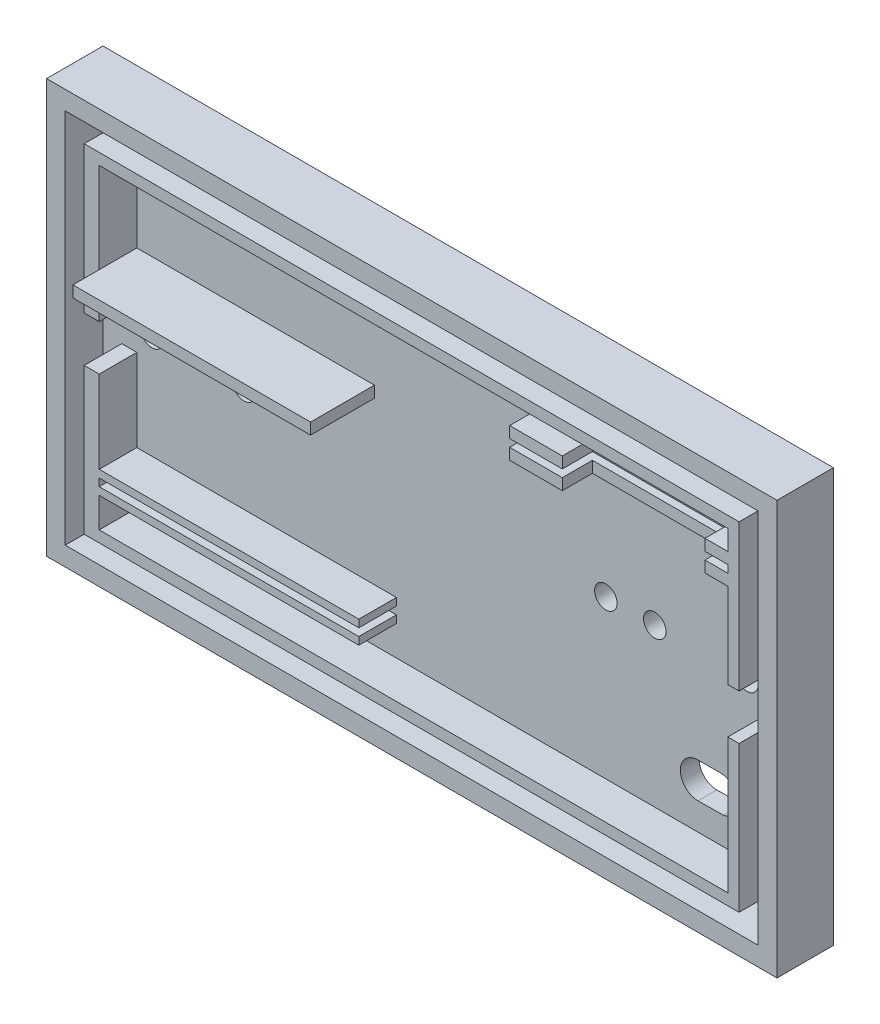
SolidWorks part; units mm, degrees
ref_plane "Plano frontal" through (0, 0, 0) normal (0, 0, 1) x (1, 0, 0)
ref_plane "Plano superior" through (0, 0, 0) normal (0, 1, 0) x (1, 0, 0)
ref_plane "Plano direito" through (0, 0, 0) normal (1, 0, 0) x (0, 0, -1)
sketch "Esboço1" plane through (0, 0, 0) normal (0, 0, 1) x (1, 0, 0)
  line L1 (-72.1599, 32.7405) -> (102.0401, 32.7405)
  line L2 (-72.1599, 32.7405) -> (-72.1599, -57.2595)
  line L3 (-72.1599, -57.2595) -> (102.0401, -57.2595)
  line L4 (102.0401, 32.7405) -> (102.0401, -57.2595)
  dimension "D1" = 174.2
  dimension "D2" = 90
extrude "Ressalto-extrusão1" add sketch "Esboço1" along normal blind 10
sketch "Esboço2" plane through (0, 0, 0) normal (0, 0, -1) x (-1, 0, 0)
  line L0 (-102.0401, 32.7405) -> (72.1599, 32.7405) construction
  line L1 (82.1599, 42.7405) -> (-112.0401, 42.7405)
  line L2 (82.1599, 42.7405) -> (82.1599, -67.2595)
  line L3 (82.1599, -67.2595) -> (-112.0401, -67.2595)
  line L4 (-112.0401, 42.7405) -> (-112.0401, -67.2595)
  line L5 (72.1599, 32.7405) -> (72.1599, -57.2595) construction
  line L6 (-102.0401, -57.2595) -> (-102.0401, 32.7405) construction
  line L7 (72.1599, -57.2595) -> (-102.0401, -57.2595) construction
  line L13 (77.1999, 37.7805) -> (-107.0001, 37.7805)
  line L14 (77.1999, 37.7805) -> (77.1999, -62.2195)
  line L15 (77.1999, -62.2195) -> (-107.0001, -62.2195)
  line L16 (-107.0001, 37.7805) -> (-107.0001, -62.2195)
  point P16 (72.1599, -12.2595)
  dimension "D1" = 10
  dimension "D2" = 10
  dimension "D3" = 10
  dimension "D4" = 10
  dimension "D5" = 5.04
  dimension "D6" = 5.04
  dimension "D7" = 5.04
  dimension "D8" = 5.04
extrude "Ressalto-extrusão2" add sketch "Esboço2" against normal blind 20 separate body
sketch "Esboço3" plane through (0, 0, 0) normal (0, 0, -1) x (-1, 0, 0)
  line L1 (82.1599, 42.7405) -> (-112.0401, 42.7405)
  line L2 (82.1599, 42.7405) -> (82.1599, -67.2595)
  line L3 (82.1599, -67.2595) -> (-112.0401, -67.2595)
  line L4 (-112.0401, 42.7405) -> (-112.0401, -67.2595)
extrude "Ressalto-extrusão3" add sketch "Esboço3" along normal blind 5
sketch "Esboço5" plane through (0, 0, 10) normal (0, 0, 1) x (1, 0, 0)
  line L0 (-72.1599, 32.7405) -> (-72.1599, -57.2595) construction
  line L1 (102.0401, -57.2595) -> (102.0401, 32.7405) construction
  line L2 (-102.7254, -12.2595) -> (207.6233, -12.2595) construction
  line L3 (-72.1599, -57.2595) -> (102.0401, -57.2595) construction
  line L4 (-72.1599, 32.7405) -> (-72.1599, -57.2595) construction
  line L6 (102.0401, 32.7405) -> (-72.1599, 32.7405) construction
  line L10 (102.0401, -57.2595) -> (102.0401, 32.7405) construction
  circle A0 centre (-64.1599, -12.2595) radius 3
  circle A1 centre (94.0401, -12.2595) radius 3
  circle A2 centre (-39.6599, -12.2595) radius 3
  circle A3 centre (69.5401, -12.2595) radius 3
  circle A4 centre (56.5401, -12.2595) radius 3
  dimension "D1" = 8
  dimension "D5" = 32.5
  dimension "D8" = 6
  dimension "D9" = 6
  dimension "D12" = 6
  dimension "D11" = 6
  dimension "D14" = 6
  dimension "D2" = 8
  dimension "D3" = 45
  dimension "D4" = 45
  dimension "D6" = 32.5
  dimension "D10" = 45
  dimension "D13" = 13
  dimension "D15" = 45
extrude "Corte-extrusão1" cut sketch "Esboço5" against normal blind 20
sketch3d "3DSketch1"
  point P0 (-63.0804, 12.5723, 10)
ref_plane "Plano1" through (0, 0, 10) normal (0, 0, 1) x (1, 0, 0)
sketch "Esboço6" plane through (0, 0, 10) normal (0, 0, 1) x (1, 0, 0)
  line L1 (-68.1599, 5.7405) -> (-4.9785, 5.7405)
  line L2 (-68.1599, 5.7405) -> (-68.1599, 2.7405)
  line L3 (-68.1599, 2.7405) -> (-4.9785, 2.7405)
  line L4 (-4.9785, 5.7405) -> (-4.9785, 2.7405)
  line L5 (102.0401, 32.7405) -> (-72.1599, 32.7405) construction
  line L6 (-72.1599, 32.7405) -> (-72.1599, -57.2595) construction
  dimension "D1" = 27
  dimension "3" = 3
  dimension "D2" = 4
extrude "Ressalto-extrusão4" add sketch "Esboço6" along normal blind 17
sketch "Esboço7" plane through (0, 0, 10) normal (0, 0, 1) x (1, 0, 0)
  line L1 (-69.1499, -42.2298) -> (0.8501, -42.2298)
  line L2 (-69.1499, -42.2298) -> (-69.1499, -40.2298)
  line L3 (-69.1499, -40.2298) -> (0.8501, -40.2298)
  line L4 (0.8501, -42.2298) -> (0.8501, -40.2298)
  line L6 (-69.1499, -46.2298) -> (0.8501, -46.2298)
  line L7 (-69.1499, -46.2298) -> (-69.1499, -44.2298)
  line L8 (-69.1499, -44.2298) -> (0.8501, -44.2298)
  line L9 (0.8501, -46.2298) -> (0.8501, -44.2298)
  line L10 (98.9601, 16.4084) -> (40.9601, 16.4084)
  line L11 (98.9601, 16.4084) -> (98.9601, 19.4084)
  line L12 (98.9601, 19.4084) -> (40.9601, 19.4084)
  line L13 (40.9601, 16.4084) -> (40.9601, 19.4084)
  line L15 (98.9601, 21.4084) -> (40.9601, 21.4084)
  line L16 (98.9601, 21.4084) -> (98.9601, 24.4084)
  line L17 (98.9601, 24.4084) -> (40.9601, 24.4084)
  line L18 (40.9601, 21.4084) -> (40.9601, 24.4084)
  line L21 (-72.1599, 32.7405) -> (-72.1599, -57.2595) construction
  line L22 (102.0401, -57.2595) -> (102.0401, 32.7405) construction
  line L23 (102.0401, -57.2595) -> (102.0401, 32.7405) construction
  dimension "D1" = 70
  dimension "D2" = 70
  dimension "D3" = 2
  dimension "D4" = 2
  dimension "D5" = 2
  dimension "D6" = 58
  dimension "D7" = 58
  dimension "D8" = 3
  dimension "D9" = 3
  dimension "D10" = 2
  dimension "D11" = 3.01
  dimension "D12" = 3.01
  dimension "D13" = 3.08
  dimension "D14" = 3.08
extrude "Ressalto-extrusão5" add sketch "Esboço7" along normal blind 10
sketch3d "3DSketch2"
  point P0 (-47.4759, -46.2298, 17.5608)
ref_plane "Plano2" through (0, -46.2298, 0) normal (0, -1, 0) x (1, 0, 0)
sketch "Esboço10" plane through (0, -46.2298, 0) normal (0, -1, 0) x (1, 0, 0)
  line L0 (40.9601, 20) -> (40.9601, 10) construction
  line L1 (54.9601, 27) -> (92.8801, 27)
  line L2 (54.9601, 27) -> (54.9601, 12)
  line L3 (54.9601, 12) -> (92.8801, 12)
  line L4 (92.8801, 27) -> (92.8801, 12)
  line L7 (-69.1499, 10) -> (0.8501, 10) construction
  line L8 (98.9601, 20) -> (98.9601, 10) construction
  point P6 (92.8801, 19.5)
  dimension "D1" = 14
  dimension "D2" = 6.08
  dimension "D3" = 2
extrude "Corte-extrusão2" cut sketch "Esboço10" against normal blind 75
sketch "Esboço11" plane through (0, 0, 10) normal (0, 0, 1) x (1, 0, 0)
  line L0 (81.0401, -37.5595) -> (87.0401, -37.5595)
  line L1 (81.0401, -46.9595) -> (87.8288, -46.8929)
  line L2 (-72.1599, -57.2595) -> (102.0401, -57.2595) construction
  line L3 (102.0401, -57.2595) -> (102.0401, 32.7405) construction
  arc A0 (81.0401, -37.5595) -> (81.0401, -46.9595) centre (81.0401, -42.2595) ccw
  arc A1 (87.8288, -46.8929) -> (87.0401, -37.5595) centre (87.0401, -42.2595) ccw
  dimension "D1" = 9.4
  dimension "D2" = 9.4
  dimension "D3" = 6
  dimension "D4" = 15
  dimension "D5" = 15
extrude "Corte-extrusão3" cut sketch "Esboço11" against normal blind 20
sketch "Esboço12" plane through (0, 0, 10) normal (0, 0, 1) x (1, 0, 0)
  line L0 (-64.1599, -6.2195) -> (-72.1599, -6.2195)
  line L1 (-72.1599, 32.7405) -> (-72.1599, -57.2595) construction
  line L2 (-64.1599, -18.2995) -> (-72.1599, -18.2995)
  line L3 (-72.1599, 32.7405) -> (-72.1599, -57.2595) construction
  line L4 (94.0401, -6.2195) -> (102.0401, -6.2195)
  line L7 (94.0401, -18.2995) -> (102.0401, -18.2995)
  line L10 (-72.1599, -18.2995) -> (-72.1599, -6.2195)
  line L11 (102.0401, -18.2995) -> (102.0401, -6.2195)
  arc A0 (-64.1599, -18.2995) -> (-64.1599, -6.2195) centre (-64.1599, -12.2595) ccw
  arc A1 (94.0401, -6.2195) -> (94.0401, -18.2995) centre (94.0401, -12.2595) ccw
  dimension "D1" = 12.08
  dimension "D2" = 12.08
extrude "Corte-extrusão4" [suppressed] cut sketch "Esboço12" against normal blind 7
sketch "Esboço13" plane through (0, 0, 0) normal (0, 0, 1) x (1, 0, 0)
  line L1 (-77.1999, 37.7805) -> (107.0001, 37.7805)
  line L2 (-77.1999, 37.7805) -> (-77.1999, -62.2195)
  line L3 (-77.1999, -62.2195) -> (107.0001, -62.2195)
  line L4 (107.0001, 37.7805) -> (107.0001, -62.2195)
  line L5 (-72.1599, 32.7405) -> (102.0401, 32.7405)
  line L6 (-72.1599, 32.7405) -> (-72.1599, -57.2595)
  line L7 (-72.1599, -57.2595) -> (102.0401, -57.2595)
  line L8 (102.0401, 32.7405) -> (102.0401, -57.2595)
extrude "Ressalto-extrusão6" add sketch "Esboço13" along normal blind 10
sketch "Esboço14" plane through (0, 0, 10) normal (0, 0, 1) x (1, 0, 0)
  line L0 (107.0001, 37.7805) -> (-77.1999, 37.7805) construction
  line L1 (101.9601, -57.1795) -> (-72.1599, -57.1795)
  line L2 (101.9601, -57.1795) -> (101.9601, -18.2995)
  line L3 (101.9601, 32.7405) -> (-72.1599, 32.7405)
  line L4 (-72.1599, -57.1795) -> (-72.1599, -18.2995)
  line L5 (-68.1599, 29.7405) -> (98.9601, 29.7405)
  line L6 (-68.1599, 29.7405) -> (-68.1599, -6.2195)
  line L7 (-68.1599, -54.1795) -> (98.9601, -54.1795)
  line L8 (98.9601, 29.7405) -> (98.9601, -6.2195)
  line L9 (-77.1999, 37.7805) -> (-77.1999, -62.2195) construction
  line L10 (107.0001, -62.2195) -> (107.0001, 37.7805) construction
  line L11 (107.0001, -62.2195) -> (-77.1999, -62.2195) construction
  line L12 (101.9601, -6.2195) -> (98.9601, -6.2195)
  line L13 (101.9601, -18.2995) -> (98.9601, -18.2995)
  line L14 (94.0401, -12.2595) -> (119.946, -12.2595) construction
  line L15 (98.9601, -18.2995) -> (98.9601, -54.1795)
  line L16 (101.9601, -6.2195) -> (101.9601, 32.7405)
  line L17 (-68.1599, -6.2195) -> (-72.1599, -6.2195)
  line L18 (-68.1599, -18.2995) -> (-72.1599, -18.2995)
  line L19 (-68.1599, -18.2995) -> (-68.1599, -54.1795)
  line L20 (-72.1599, -6.2195) -> (-72.1599, 32.7405)
  dimension "D1" = 5.04
  dimension "D2" = 5.04
  dimension "D3" = 5.04
  dimension "D4" = 5.04
  dimension "D5" = 3
  dimension "D6" = 3
  dimension "D7" = 4
  dimension "D8" = 3
  dimension "D9" = 12.08
  dimension "D10" = 6.04
extrude "Ressalto-extrusão7" add sketch "Esboço14" along normal blind 10
sketch "Esboço17" plane through (0, -67.2595, 0) normal (0, -1, 0) x (1, 0, 0)
  line L0 (112.0401, -5) -> (112.0401, 20) construction
  line L1 (-82.1599, -5) -> (112.0401, -5)
  line L2 (-82.1599, -5) -> (-82.1599, 5)
  line L3 (-82.1599, 5) -> (112.0401, 5)
  line L4 (112.0401, -5) -> (112.0401, 5)
  dimension "D1" = 10
extrude "Corte-extrusão5" cut sketch "Esboço17" against normal blind 200
sketch "Esboço18" plane through (0, 0, 10) normal (0, 0, 1) x (1, 0, 0)
  line L0 (-64.1599, -15.2595) -> (-72.1599, -15.2595)
  line L1 (-72.1599, -18.2995) -> (-72.1599, -57.1795) construction
  line L2 (-72.1599, -15.2595) -> (-72.1599, -9.2595)
  line L3 (-72.1599, -9.2595) -> (-64.1599, -9.2595)
  line L4 (-64.1599, -9.2595) -> (-64.1599, -15.2595)
  line L5 (94.0401, -9.2595) -> (98.9601, -9.2595)
  line L6 (98.9601, -6.2195) -> (98.9601, 16.4084) construction
  line L7 (98.9601, -9.2595) -> (98.9601, -15.2595)
  line L8 (98.9601, -15.2595) -> (94.0401, -15.2595)
  line L9 (94.0401, -15.2595) -> (94.0401, -9.2595)
  circle A0 centre (-64.1599, -12.2595) radius 3 construction
  circle A1 centre (94.0401, -12.2595) radius 3 construction
extrude "Corte-extrusão6" [suppressed] cut sketch "Esboço18" along normal blind 200
